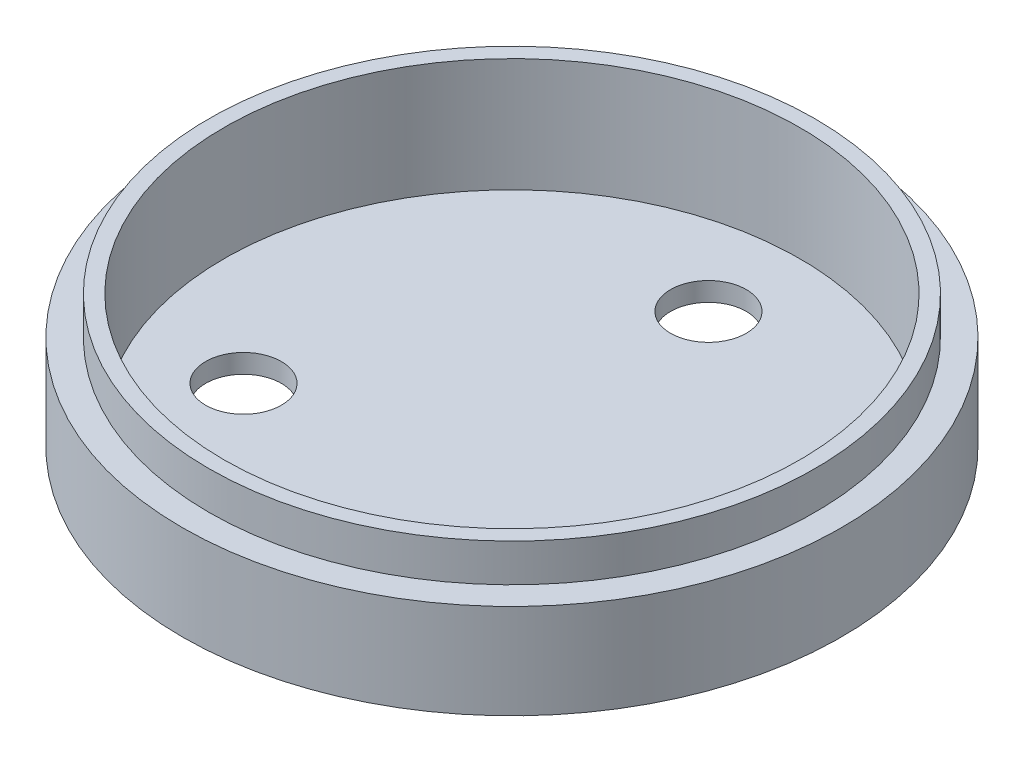
SolidWorks part; units mm, degrees
ref_plane "Front Plane" through (0, 0, 0) normal (0, 0, 1) x (1, 0, 0)
ref_plane "Top Plane" through (0, 0, 0) normal (0, 1, 0) x (1, 0, 0)
ref_plane "Right Plane" through (0, 0, 0) normal (1, 0, 0) x (0, 0, -1)
sketch "Sketch1" plane through (0, 0, 0) normal (0, 1, 0) x (1, 0, 0)
  circle A0 centre (0, 0) radius 51.875 construction
  circle A2 centre (0, 51.875) radius 10
  circle A3 centre (44.9266, -25.9366) radius 10
  circle A4 centre (-44.9236, -25.9384) radius 10
  circle A5 centre (0, 0) radius 87
  point P12 (0.001, 0)
extrude "Boss-Extrude1" add sketch "Sketch1" along normal blind 5
sketch "Sketch2" plane through (0, 5, 0) normal (0, 1, 0) x (1, 0, 0)
  circle A0 centre (0, 0) radius 80
  circle A1 centre (0, 0) radius 76
  dimension "D1" = 4
extrude "Boss-Extrude2" add sketch "Sketch2" along normal blind 30
sketch "Sketch3" plane through (0, 5, 0) normal (0, 1, 0) x (1, 0, 0)
  circle A0 centre (0, 0) radius 80 construction
  circle A1 centre (0, 0) radius 87 construction
  circle A2 centre (0, 0) radius 80
  circle A3 centre (0, 0) radius 87
extrude "Boss-Extrude3" add sketch "Sketch3" along normal blind 20
